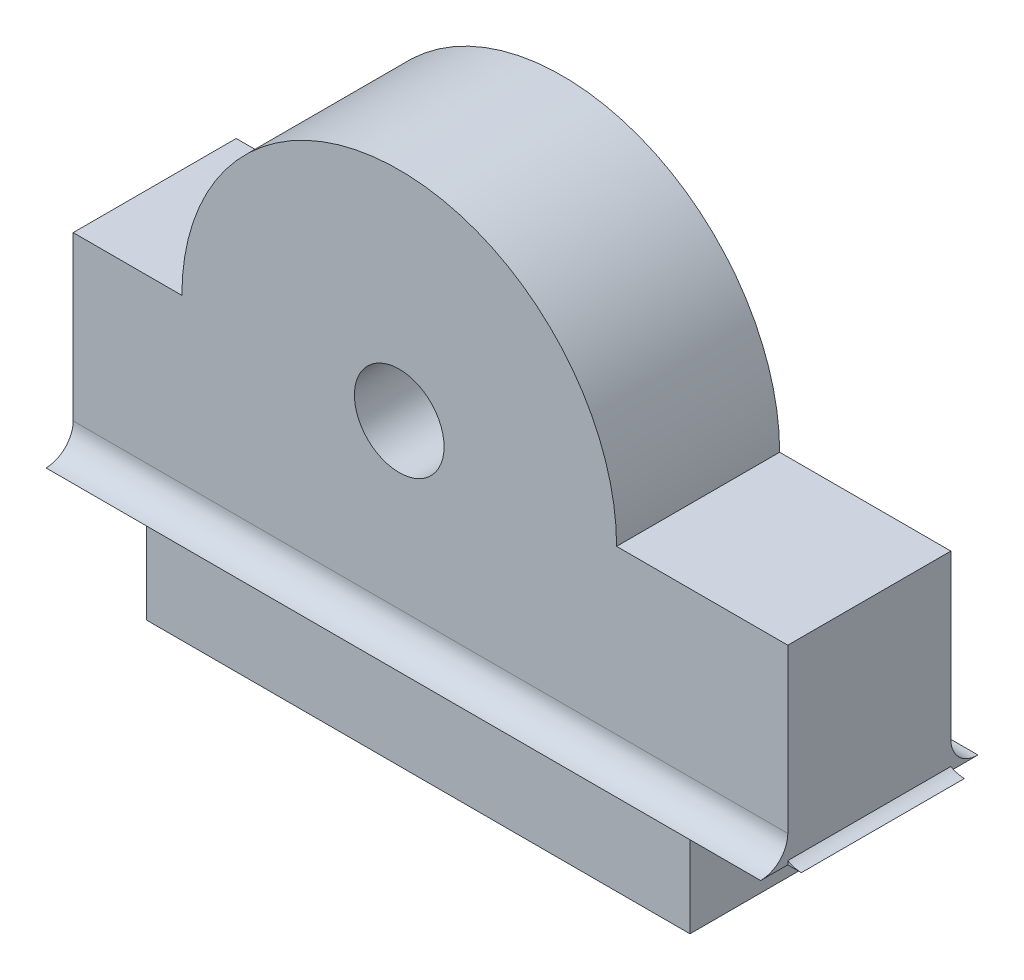
SolidWorks part; units mm, degrees
ref_plane "Front Plane" through (0, 0, 0) normal (0, 0, 1) x (1, 0, 0)
ref_plane "Top Plane" through (0, 0, 0) normal (0, 1, 0) x (1, 0, 0)
ref_plane "Right Plane" through (0, 0, 0) normal (1, 0, 0) x (0, 0, -1)
sketch "Sketch1" plane through (0, 0, 0) normal (0, 0, 1) x (1, 0, 0)
  line L0 (0, 0) -> (20, 0)
  line L1 (0, 0) -> (0, 4)
  line L2 (20, 0) -> (20, 4)
  line L3 (0, 4) -> (-2.7, 4)
  line L4 (23.6, 11) -> (23.6, 4)
  line L5 (-2.7, 4) -> (-2.7, 11)
  line L6 (-2.7, 11) -> (1.3, 11)
  line L7 (17.3, 11) -> (23.6, 11)
  line L8 (23.6, 4) -> (20, 4)
  line L9 (1.3, 11) -> (9.3, 11) construction
  line L10 (12.9373, 11) -> (9.3, 11) construction
  arc A0 (17.3, 11) -> (1.3, 11) centre (9.3, 11) ccw
  circle A1 centre (9.3, 11) radius 2.9
  point P19 (10, 0)
  point P22 (9.3, 11)
  dimension "D1" = 7
  dimension "D5" = 9.3
  dimension "D6" = 20
  dimension "D2" = 8
  dimension "D4" = 5.8
  dimension "D3" = 2.7
  dimension "D7" = 23.6
  dimension "D9" = 4
extrude "Boss-Extrude1" add sketch "Sketch1" along normal blind 6
sketch "Sketch2" plane through (-2.7, 0, 0) normal (-1, 0, 0) x (0, 0, 1)
  line L0 (3, 0) -> (3, 7) construction
  line L1 (6, 4) -> (6, 5)
  line L2 (6, 4) -> (7, 4)
  line L3 (0, 4) -> (-1, 4)
  line L4 (0, 4) -> (0, 5)
  arc A0 (6, 5) -> (7, 4) centre (7, 5) ccw
  arc A1 (0, 5) -> (-1, 4) centre (-1, 5) cw
  dimension "D1" = 1
  dimension "D2" = 1
  dimension "D3" = 6
  dimension "D4" = 3
  dimension "D5" = 4
extrude "Boss-Extrude2" add sketch "Sketch2" against normal up to surface (26.3 mm away) up to face at (23.6, 7.5, 3)
sketch "Sketch4" plane through (0, 0, 6) normal (0, 0, 1) x (1, 0, 0)
  line L0 (10.8, 0) -> (10.8, 7) construction
  line L1 (23.1, 4) -> (23.1, 5)
  line L2 (23.1, 4) -> (24.1, 4)
  line L3 (-1.5, 4) -> (-2.5, 4)
  line L4 (-1.5, 4) -> (-1.5, 5)
  arc A0 (23.1, 5) -> (24.1, 4) centre (24.1, 5) ccw
  arc A1 (-1.5, 5) -> (-2.5, 4) centre (-2.5, 5) cw
  dimension "D1" = 1
  dimension "D2" = 1
  dimension "D3" = 10.8
  dimension "D4" = 12.3
  dimension "D5" = 4
extrude "Boss-Extrude3" add sketch "Sketch4" against normal up to surface (6 mm away) up to face at (12.2, 11, 0)
sketch "Sketch5" plane through (0, 0, 0) normal (0, 0, -1) x (-1, 0, 0)
  line L0 (-9.3, 13.9) -> (-9.3, 8.1) construction
  circle A0 centre (-9.3, 11) radius 2.9 construction
  circle A1 centre (-9.3, 11) radius 1.65
  circle A2 centre (-9.3, 11) radius 2.9
  dimension "D1" = 3.3
  dimension "D2" = 5.8
extrude "Boss-Extrude4" add sketch "Sketch5" against normal blind 3
sketch "Sketch6" plane through (0, 0, 6) normal (0, 0, 1) x (1, 0, 0)
  circle A0 centre (9.3, 11) radius 1.65
  circle A1 centre (9.3, 11) radius 2.9
  dimension "D1" = 3.3
  dimension "D2" = 5.8
sketch "Sketch7" plane through (0, 0, 0) normal (0, 0, -1) x (-1, 0, 0)
  circle A0 centre (-9.3, 11) radius 2.9
  dimension "D1" = 5.8
extrude "Cut-Extrude1" cut sketch "Sketch7" against normal blind 10
extrude "Boss-Extrude5" add sketch "Sketch6" against normal blind 3
equation "\"D4@Sketch1\"= 5.5 + \"tol1@parametersSketch@prostheticParameters.SLDPRT\""
equation "\"D1@Sketch5\"= 3 + \"tol1@parametersSketch@prostheticParameters.SLDPRT\""
equation "\"D2@Sketch5\"= 5.5 + \"tol1@parametersSketch@prostheticParameters.SLDPRT\""
equation "\"D1@Sketch6\"= 3 + \"tol1@parametersSketch@prostheticParameters.SLDPRT\""
equation "\"D2@Sketch6\"= 5.5 + \"tol1@parametersSketch@prostheticParameters.SLDPRT\""
equation "\"D1@Sketch7\"= 5.5 + \"tol1@parametersSketch@prostheticParameters.SLDPRT\""
